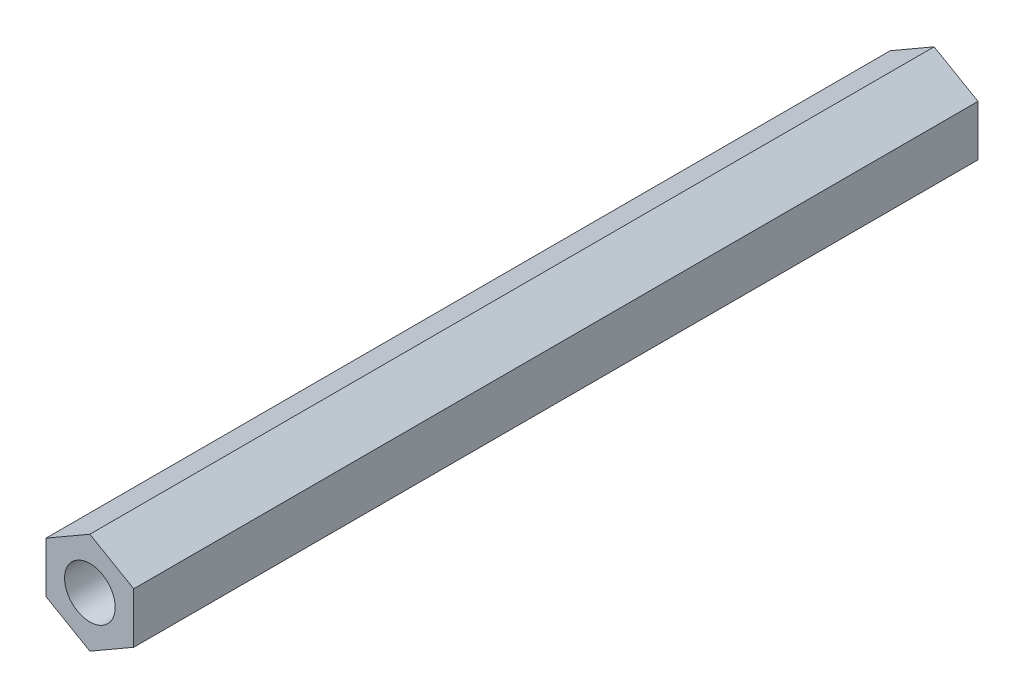
SolidWorks part; units mm, degrees
ref_plane "前视基准面" through (0, 0, 0) normal (0, 0, 1) x (1, 0, 0)
ref_plane "上视基准面" through (0, 0, 0) normal (0, 1, 0) x (1, 0, 0)
ref_plane "右视基准面" through (0, 0, 0) normal (1, 0, 0) x (0, 0, -1)
sketch "草图1" plane through (0, 0, 0) normal (0, 0, 1) x (1, 0, 0)
  line L1 (-12.9585, 63.6886) -> (-10.3604, 65.1886)
  line L2 (-10.3604, 65.1886) -> (-10.3604, 68.1886)
  line L3 (-10.3604, 68.1886) -> (-12.9585, 69.6886)
  line L4 (-12.9585, 69.6886) -> (-15.5566, 68.1886)
  line L5 (-15.5566, 68.1886) -> (-15.5566, 65.1886)
  line L6 (-15.5566, 65.1886) -> (-12.9585, 63.6886)
  circle A0 centre (-12.9585, 66.6886) radius 2.5981 construction
  circle A1 centre (-12.9585, 66.6886) radius 1.5
  point P9 (-12.9585, 66.6886)
  dimension "D2" = 3
  dimension "D1" = 3
extrude "凸台-拉伸1" add sketch "草图1" along normal blind 50
